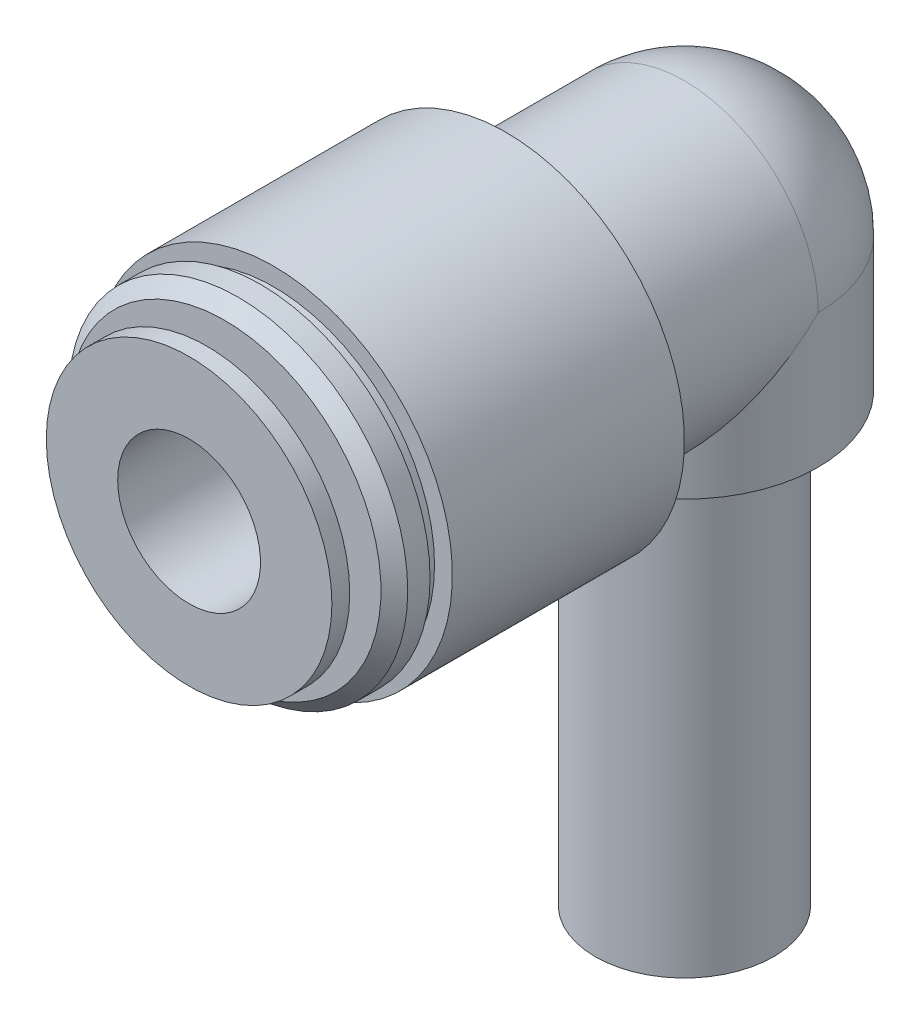
SolidWorks part; units mm, degrees
ref_plane "Спереди" through (0, 0, 0) normal (0, 0, 1) x (1, 0, 0)
ref_plane "Сверху" through (0, 0, 0) normal (0, 1, 0) x (1, 0, 0)
ref_plane "Справа" through (0, 0, 0) normal (1, 0, 0) x (0, 0, -1)
sketch "Эскиз1" plane through (0, 0, 0) normal (0, 1, 0) x (1, 0, 0)
  circle A0 centre (0, 0) radius 5
  circle A1 centre (0, 0) radius 4
  dimension "D1" = 8
  dimension "D2" = 10
extrude "Бобышка-Вытянуть1" add sketch "Эскиз1" along normal blind 25
sketch "Эскиз2" plane through (0, 0, 0) normal (0, 0, 1) x (1, 0, 0)
  line L0 (0, 25) -> (0, 40)
  line L1 (5, 25) -> (-5, 25) construction
  line L2 (0, 25) -> (7.5, 25)
  line L3 (7.5, 25) -> (7.5, 32.5)
  arc A0 (7.5, 32.5) -> (0, 40) centre (0, 32.5) ccw
revolve "Повернуть1" add sketch "Эскиз2" angle 360 about L0
sketch "Эскиз3" plane through (0, 0, 0) normal (0, 0, 1) x (1, 0, 0)
  circle A1 centre (0, 32.5) radius 7.5
extrude "Бобышка-Вытянуть2" add sketch "Эскиз3" along normal blind 10
sketch "Эскиз4" plane through (0, 0, 10) normal (0, 0, 1) x (1, 0, 0)
  circle A0 centre (0, 32.5) radius 10
extrude "Бобышка-Вытянуть3" add sketch "Эскиз4" along normal blind 13
sketch "Эскиз5" plane through (0, 0, 0) normal (1, 0, 0) x (0, 0, -1)
  line L9 (-26.75, 24.5) -> (-26.75, 26.5)
  line L11 (-27.75, 28.5) -> (-27.75, 24.5)
  line L13 (-27.75, 24.5) -> (-26.75, 24.5)
  line L15 (-25.75, 26.5) -> (-25.75, 23.75)
  line L16 (-25, 23) -> (-23.75, 23)
  line L17 (-25.75, 23.75) -> (-25, 23)
  line L18 (-23.75, 23) -> (-23.75, 23.5)
  line L19 (-23.75, 23.5) -> (-23, 23.5)
  line L20 (-23, 23.5) -> (-23, 28.5)
  line L21 (-27.75, 28.5) -> (-23, 28.5)
  line L22 (-26.75, 26.5) -> (-25.75, 26.5)
  line L23 (-23, 32.5) -> (-33.2854, 32.5) construction
  line L24 (-23, 42.5) -> (-23, 22.5) construction
  point P13 (-25.75, 23)
  dimension "D4" = 0.75
  dimension "D5" = 0.75
  dimension "D6" = 2
revolve "Повернуть3" add sketch "Эскиз5" angle 360 about L23
sketch "Эскиз6" plane through (0, 0, 27.75) normal (0, 0, 1) x (1, 0, 0)
  circle A0 centre (0, 32.5) radius 4
  dimension "D1" = 8
extrude "Вырез-Вытянуть1" cut sketch "Эскиз6" against normal blind 28
